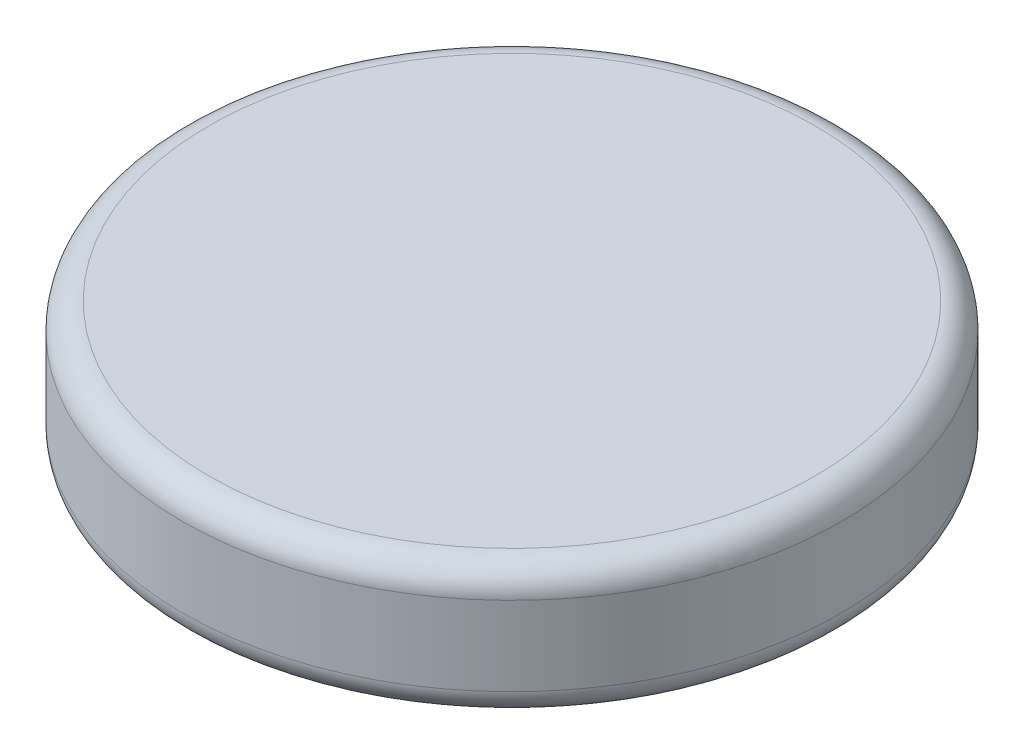
SolidWorks part; units mm, degrees
material "Caucho de silicio"
ref_plane "Alzado" through (0, 0, 0) normal (0, 0, 1) x (1, 0, 0)
ref_plane "Planta" through (0, 0, 0) normal (0, 1, 0) x (1, 0, 0)
ref_plane "Vista lateral" through (0, 0, 0) normal (1, 0, 0) x (0, 0, -1)
sketch "Croquis1" plane through (0, 0, 0) normal (0, 1, 0) x (1, 0, 0)
  circle A0 centre (0, 0) radius 125
  dimension "D1" = 250
extrude "Saliente-Extruir1" add sketch "Croquis1" along normal blind 50
fillet "Redondeo2" radius 10 2 edges at (0, 0, 125) (0, 50, 125)
